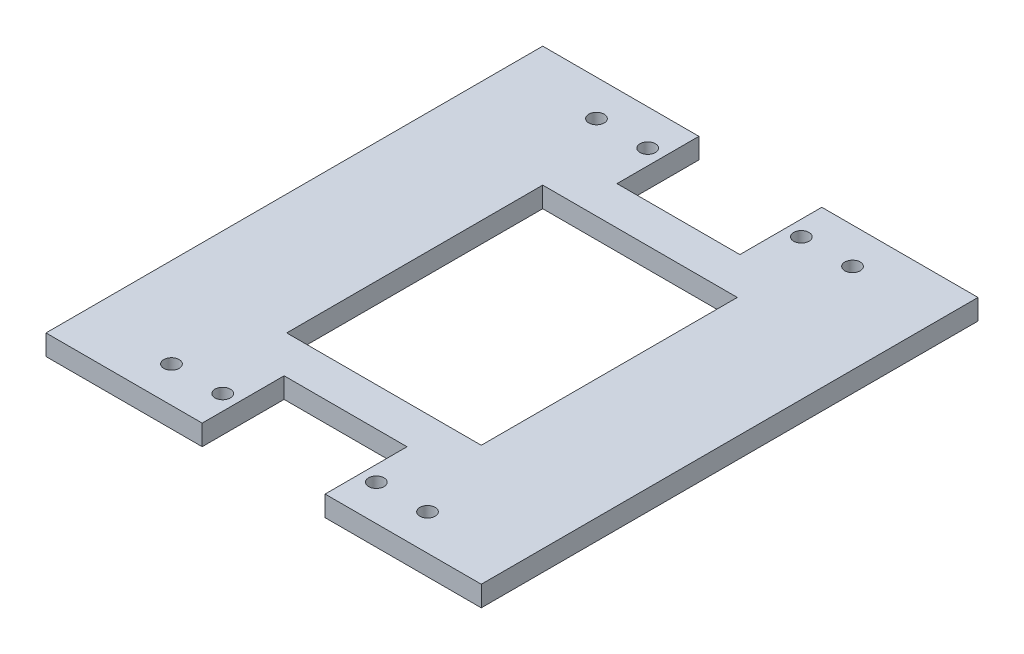
SolidWorks part; units mm, degrees
material "Thornel Mat VMA"
ref_plane "前视基准面" through (0, 0, 0) normal (0, 0, 1) x (1, 0, 0)
ref_plane "上视基准面" through (0, 0, 0) normal (0, 1, 0) x (1, 0, 0)
ref_plane "右视基准面" through (0, 0, 0) normal (1, 0, 0) x (0, 0, -1)
other "Configuration Table"
sketch "草图1" plane through (0, 0, 0) normal (0, 1, 0) x (1, 0, 0)
  line L0 (-12, 48.5) -> (-12, 32.5)
  line L1 (-42.5, 48.5) -> (-12, 48.5)
  line L2 (-42.5, 48.5) -> (-42.5, -48.5)
  line L3 (-42.5, -48.5) -> (-12, -48.5)
  line L4 (42.5, 48.5) -> (42.5, -48.5)
  line L5 (-42.5, 48.5) -> (42.5, -48.5) construction
  line L6 (-42.5, -48.5) -> (42.5, 48.5) construction
  line L7 (-12, 32.5) -> (12, 32.5)
  line L8 (12, 32.5) -> (12, 48.5)
  line L9 (12, 48.5) -> (42.5, 48.5)
  line L10 (0, 0) -> (0, -50000) construction
  line L11 (0, 0) -> (-50000, 0) construction
  line L12 (12, -32.5) -> (12, -48.5)
  line L13 (-12, -32.5) -> (12, -32.5)
  line L14 (-12, -48.5) -> (-12, -32.5)
  line L15 (12, -48.5) -> (42.5, -48.5)
  line L17 (-19, 25) -> (19, 25)
  line L18 (-19, 25) -> (-19, -25)
  line L19 (-19, -25) -> (19, -25)
  line L20 (19, 25) -> (19, -25)
  line L21 (-19, 25) -> (19, -25) construction
  line L22 (-19, -25) -> (19, 25) construction
  circle A0 centre (15, 41.5) radius 1.5
  circle A1 centre (25, 41.5) radius 1.5
  circle A2 centre (-25, 41.5) radius 1.5
  circle A3 centre (-15, 41.5) radius 1.5
  circle A4 centre (25, -41.5) radius 1.5
  circle A5 centre (15, -41.5) radius 1.5
  circle A6 centre (-15, -41.5) radius 1.5
  circle A7 centre (-25, -41.5) radius 1.5
  point P0 (0, 0)
  point P22 (0, 0)
  dimension "D6" = 3
  dimension "D7" = 7
  dimension "D8" = 38
  dimension "D10" = 10
  dimension "D1" = 97
  dimension "D2" = 85
  dimension "D3" = 12
  dimension "D4" = 12
  dimension "D5" = 16
  dimension "D9" = 50
extrude "凸台-拉伸1" add sketch "草图1" along normal blind 4
